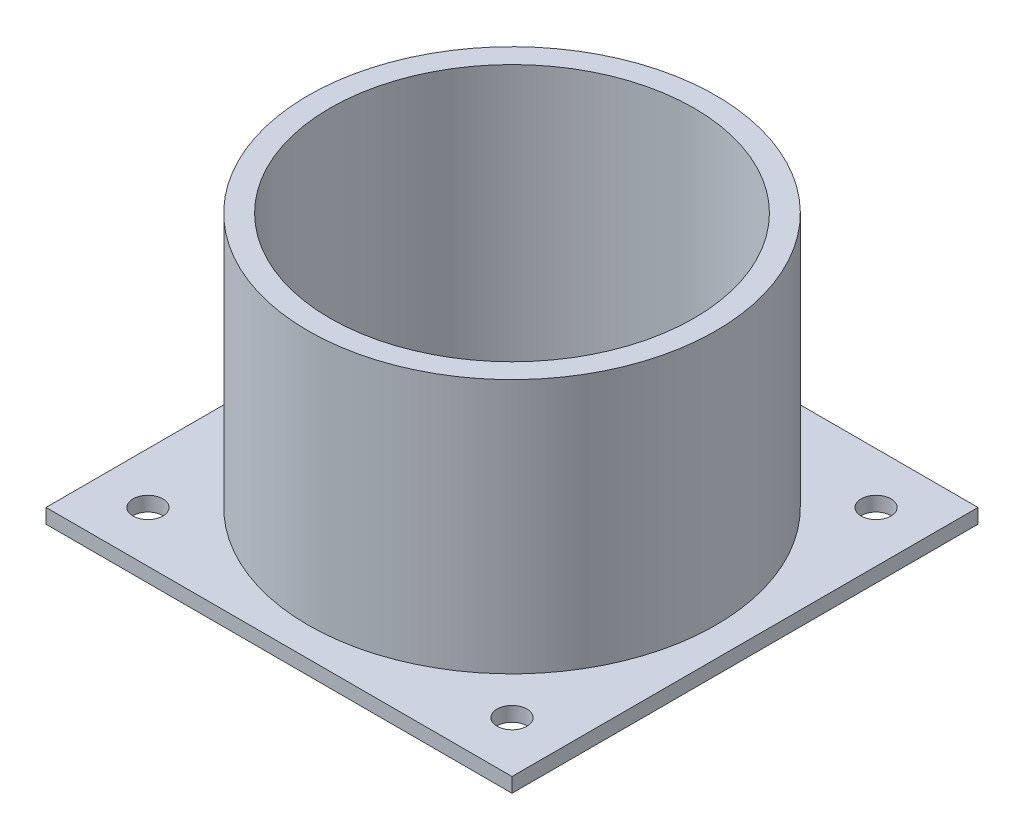
SolidWorks part; units mm, degrees
ref_plane "前视基准面" through (0, 0, 0) normal (0, 0, 1) x (1, 0, 0)
ref_plane "上视基准面" through (0, 0, 0) normal (0, 1, 0) x (1, 0, 0)
ref_plane "右视基准面" through (0, 0, 0) normal (1, 0, 0) x (0, 0, -1)
sketch "草图1" plane through (0, 0, 0) normal (0, 1, 0) x (1, 0, 0)
  line L1 (-23.9241, 18.7161) -> (40.0759, 18.7161)
  line L2 (-23.9241, 18.7161) -> (-23.9241, -45.2839)
  line L3 (-23.9241, -45.2839) -> (40.0759, -45.2839)
  line L4 (40.0759, 18.7161) -> (40.0759, -45.2839)
  dimension "D1" = 64
  dimension "D2" = 64
extrude "凸台-拉伸1" add sketch "草图1" along normal blind 2
sketch "草图2" plane through (0, 2, 0) normal (0, 1, 0) x (1, 0, 0)
  line L0 (40.0759, 18.7161) -> (-23.9241, 18.7161) construction
  line L1 (-23.9241, 18.7161) -> (-23.9241, -45.2839) construction
  line L3 (-16.9241, 11.7161) -> (33.0759, 11.7161) construction
  line L4 (-16.9241, 11.7161) -> (-16.9241, -38.2839) construction
  line L5 (-16.9241, -38.2839) -> (33.0759, -38.2839) construction
  line L6 (33.0759, 11.7161) -> (33.0759, -38.2839) construction
  circle A0 centre (-16.9241, 11.7161) radius 2.05
  circle A1 centre (33.0759, 11.7161) radius 2.05
  circle A2 centre (-16.9241, -38.2839) radius 2.05
  circle A3 centre (33.0759, -38.2839) radius 2.05
  circle A4 centre (8.0759, -13.2839) radius 25
  point P0 (8.0759, 18.7161)
  point P1 (-23.9241, -13.2839)
  point P4 (8.0759, -13.2839)
  point P11 (-16.9241, -13.2839)
  point P12 (8.0759, 11.7161)
  dimension "D1" = 50
  dimension "D2" = 50
extrude "切除-拉伸1" cut sketch "草图2" against normal blind 2 contours A0 | A2 | A4 | A1 | A3
sketch "草图3" plane through (0, 2, 0) normal (0, 1, 0) x (1, 0, 0)
  line L0 (-23.9241, 18.7161) -> (-23.9241, -45.2839) construction
  line L1 (40.0759, 18.7161) -> (-23.9241, 18.7161) construction
  line L2 (40.0759, -45.2839) -> (40.0759, 18.7161) construction
  line L3 (-23.9241, -45.2839) -> (40.0759, -45.2839) construction
  line L4 (8.0759, 18.7161) -> (8.0759, -45.2839) construction
  line L5 (-23.9241, -13.2839) -> (40.0759, -13.2839) construction
  circle A0 centre (8.0759, -13.2839) radius 28
  circle A1 centre (8.0759, -13.2839) radius 25
  point P0 (-23.9241, -13.2839)
  point P1 (8.0759, 18.7161)
  point P4 (40.0759, -13.2839)
  point P7 (8.0759, -45.2839)
  point P16 (8.0759, -13.2839)
extrude "凸台-拉伸2" add sketch "草图3" along normal blind 35
